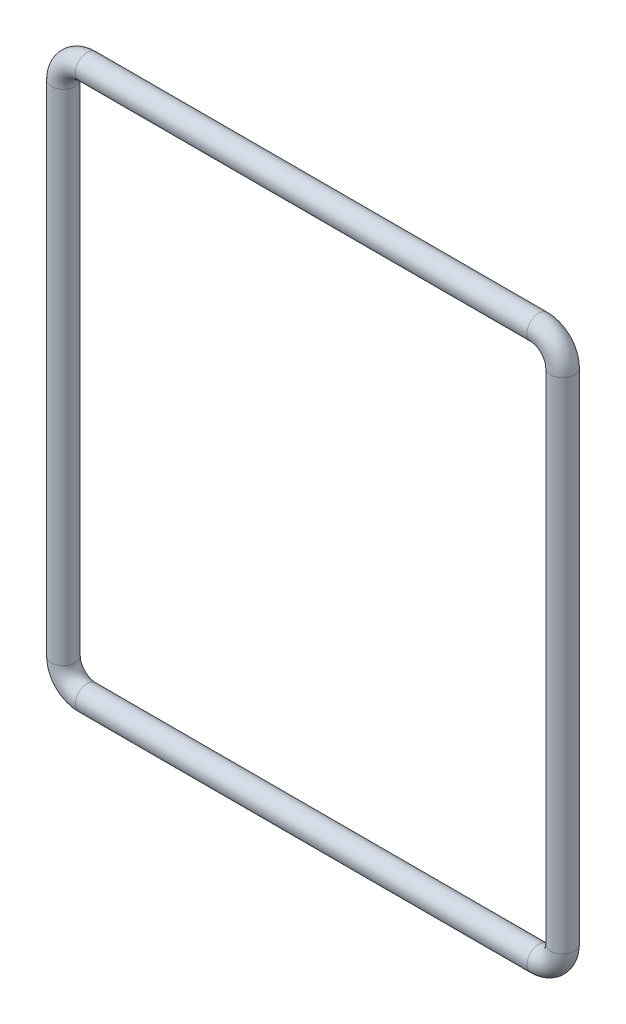
SolidWorks part; units mm, degrees
ref_plane "Face" through (0, 0, 0) normal (0, 0, 1) x (1, 0, 0)
ref_plane "Dessus" through (0, 0, 0) normal (0, 1, 0) x (1, 0, 0)
ref_plane "Droite" through (0, 0, 0) normal (1, 0, 0) x (0, 0, -1)
sketch "Esquisse1" plane through (0, 0, 0) normal (0, 0, 1) x (1, 0, 0)
  line L1 (-19, 23) -> (19, 23)
  line L2 (-21, 21) -> (-21, -21)
  line L3 (-19, -23) -> (19, -23)
  line L4 (21, 21) -> (21, -21)
  arc A0 (-21, -21) -> (-19, -23) centre (-19, -21) ccw
  arc A1 (-19, 23) -> (-21, 21) centre (-19, 21) ccw
  arc A2 (19, 23) -> (21, 21) centre (19, 21) cw
  arc A3 (19, -23) -> (21, -21) centre (19, -21) ccw
  point P4 (0, 23)
  point P6 (21, 0)
  point P11 (-21, 23)
  point P14 (21, 23)
  point P17 (21, -23)
  dimension "D3" = 2
  dimension "D4" = 2
  dimension "D1" = 46
  dimension "D2" = 42
sketch "Esquisse2" plane through (0, 0, 0) normal (0, 1, 0) x (1, 0, 0)
  circle A0 centre (21, 0) radius 1
  dimension "D1" = 2
sweep "Balayage1" add profiles "Esquisse2" path "Esquisse1"
move or copy body "Body-Move/Copy1" [suppressed] bodies to move or copy 101 parameters "D1"=0, "D2"=0, "D3"=0
